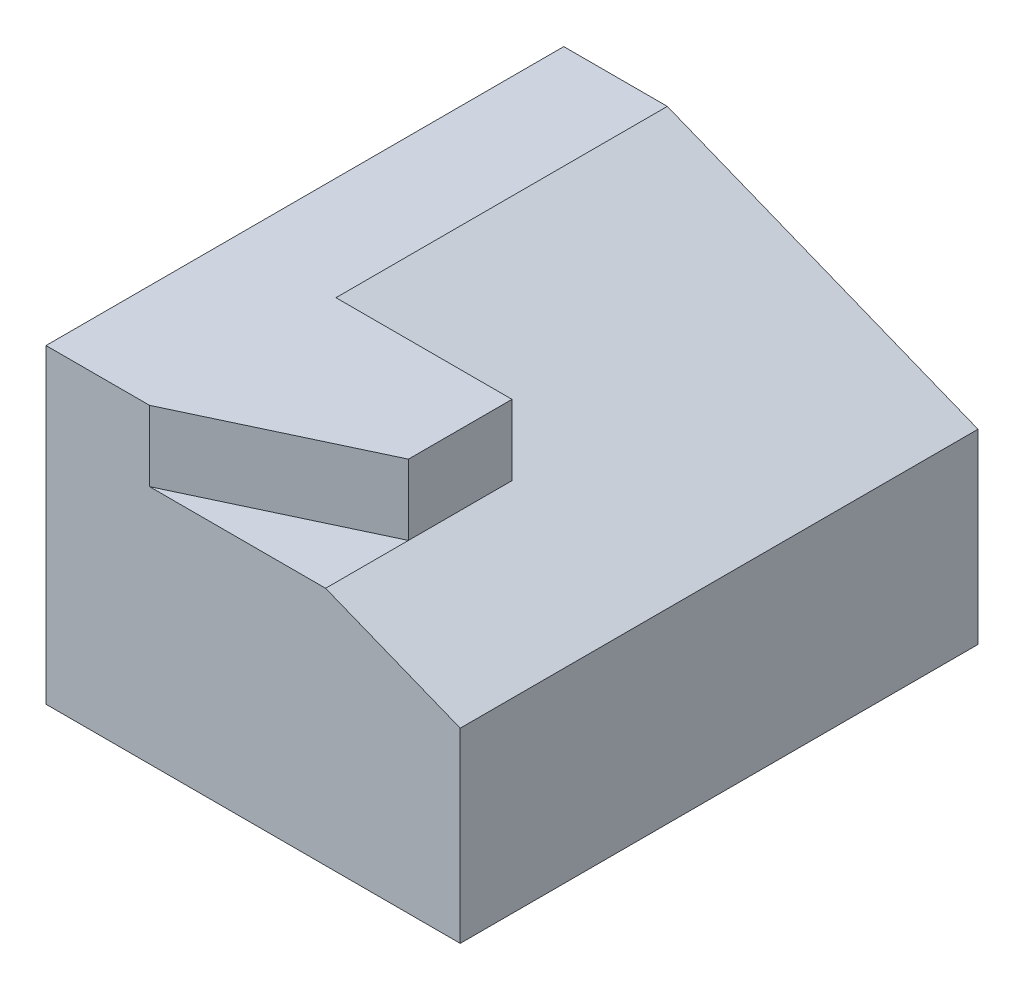
SolidWorks part; units mm, degrees
ref_plane "Спереди" through (0, 0, 0) normal (0, 0, 1) x (1, 0, 0)
ref_plane "Сверху" through (0, 0, 0) normal (0, 1, 0) x (1, 0, 0)
ref_plane "Справа" through (0, 0, 0) normal (1, 0, 0) x (0, 0, -1)
sketch "Эскиз1" plane through (0, 0, 0) normal (1, 0, 0) x (0, 0, -1)
  line L1 (-25, -15) -> (25, -15)
  line L2 (-25, -15) -> (-25, 15)
  line L3 (-25, 15) -> (25, 15)
  line L4 (25, -15) -> (25, 15)
  line L5 (-25, -15) -> (25, 15) construction
  line L6 (-25, 15) -> (25, -15) construction
  point P0 (0, 0)
  dimension "D1" = 30
  dimension "D2" = 50
extrude "Бобышка-Вытянуть1" add sketch "Эскиз1" along normal blind 40
sketch "Эскиз2" plane through (0, 0, 25) normal (0, 0, 1) x (1, 0, 0)
  line L0 (10, 15) -> (40, 3)
  line L2 (40, 15) -> (0, 15) construction
  line L3 (40, 15) -> (40, -15) construction
  line L4 (40, 3) -> (40, 15)
  line L5 (40, 15) -> (10, 15)
  dimension "D1" = 12
  dimension "D2" = 30
extrude "Вырез-Вытянуть1" cut sketch "Эскиз2" against normal through all
sketch "Эскиз3" plane through (0, -15, 0) normal (0, -1, 0) x (1, 0, 0)
  line L0 (40, 13) -> (27, 25)
  line L1 (40, 25) -> (40, -25) construction
  line L2 (40, 25) -> (0, 25) construction
  line L3 (27, 25) -> (40, 25)
  line L4 (40, 25) -> (40, 13)
  dimension "D1" = 12
  dimension "D2" = 13
extrude "Вырез-Вытянуть2" cut sketch "Эскиз3" against normal through all
sketch "Эскиз4" plane through (0, 0, 25) normal (0, 0, 1) x (1, 0, 0)
  line L1 (10, 15) -> (27, 15)
  line L2 (10, 15) -> (10, 8.2)
  line L3 (10, 8.2) -> (27, 8.2)
  line L4 (27, 15) -> (27, 8.2)
extrude "Вырез-Вытянуть3" cut sketch "Эскиз4" against normal blind 18
sketch "Эскиз5" plane through (0, 15, 0) normal (0, 1, 0) x (1, 0, 0)
  line L0 (10, -7) -> (27, -7)
  line L1 (27, -7) -> (27, -17)
  line L3 (27, -17) -> (10, -25)
  line L4 (10, -25) -> (10, -7)
  line L5 (27, -7) -> (27, -25) construction
  dimension "D1" = 10
extrude "Бобышка-Вытянуть2" add sketch "Эскиз5" against normal up to surface (6.8 mm away) up to face at (18.5, 8.2, 16)
sketch "Эскиз6" plane through (0, -15, 0) normal (0, -1, 0) x (1, 0, 0)
  line L0 (27, 25) -> (40, 13)
  line L1 (40, 13) -> (40, 25)
  line L2 (40, 25) -> (27, 25)
extrude "Бобышка-Вытянуть4" add sketch "Эскиз6" against normal up to surface (18 mm away)
